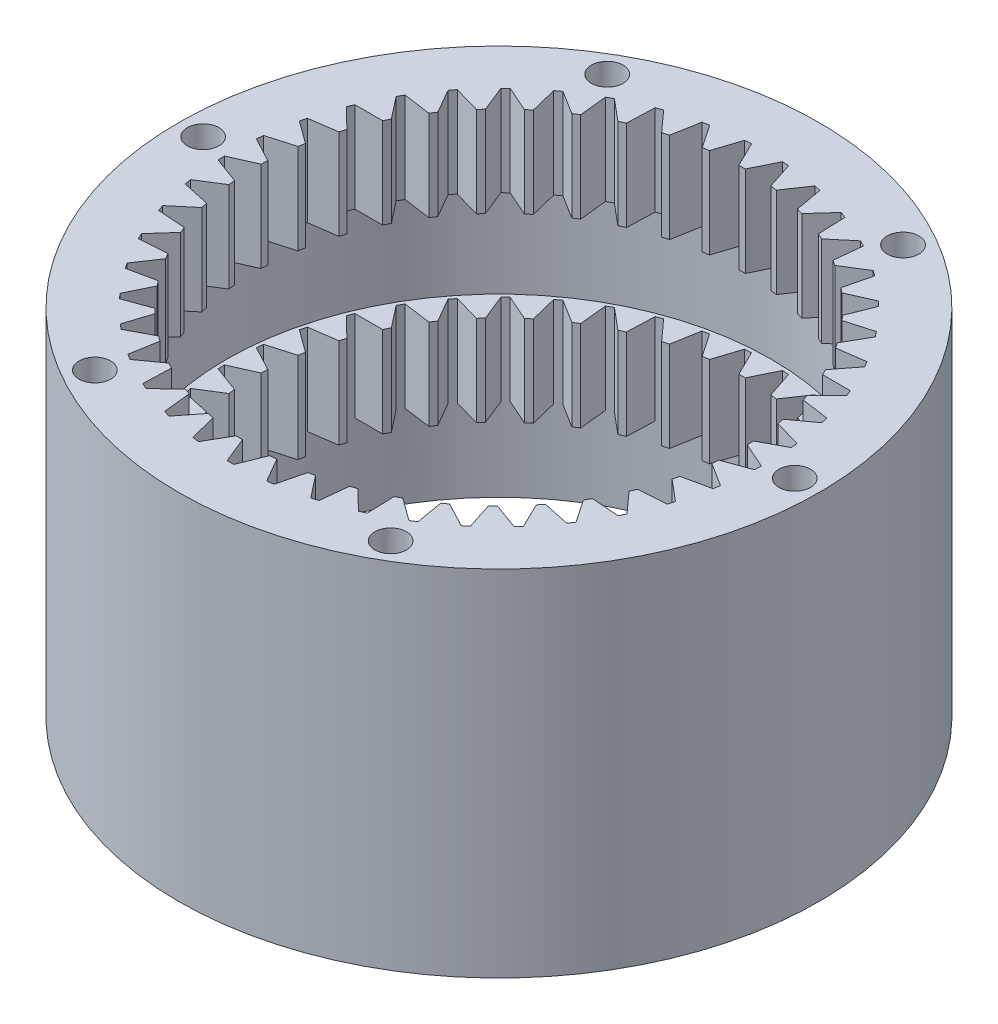
SolidWorks part; units mm, degrees
ref_plane "Plano frontal" through (0, 0, 0) normal (0, 0, 1) x (1, 0, 0)
ref_plane "Plano superior" through (0, 0, 0) normal (0, 1, 0) x (1, 0, 0)
ref_plane "Plano direito" through (0, 0, 0) normal (1, 0, 0) x (0, 0, -1)
sketch "Esboço1" plane through (0, 0, 0) normal (0, 1, 0) x (1, 0, 0)
  circle A0 centre (0, 0) radius 42.5
  circle A1 centre (0, 0) radius 35.626
  dimension "D1" = 85
  dimension "D2" = 71.252
extrude "Ressalto-extrusão1" add sketch "Esboço1" against normal blind 47
sketch "Esboço2" plane through (0, 0, 0) normal (0, 1, 0) x (1, 0, 0)
  line L0 (0, 35.626) -> (0, 32.258) construction
  line L1 (-0.4275, 32.258) -> (0.4275, 32.258)
  line L2 (-0.4275, 32.258) -> (-2.0474, 35.5671)
  line L3 (0.4275, 32.258) -> (2.0474, 35.5671)
  circle A0 centre (0, 0) radius 35.626 construction
  circle A2 centre (0, 0) radius 35.626
  arc A3 (2.0474, 35.5671) -> (-2.0474, 35.5671) centre (0, 0) ccw
  point P8 (0, 32.258)
  dimension "D1" = 3.368
  dimension "D2" = 0.855
  dimension "D3" = 26.084
  dimension "D4" = 0
extrude "Ressalto-extrusão2" add sketch "Esboço2" against normal blind 36
pattern_circular "PadrãoCircular2" count 45 over 360 about axis through (0, 0, 0) along (0, 1, 0) of "Ressalto-extrusão2"
ref_plane "Plano2" through (0, -12, 0) normal (0, 1, 0) x (1, 0, 0)
sketch "Esboço5" plane through (0, -12, 0) normal (0, 1, 0) x (1, 0, 0)
  circle A0 centre (0, 0) radius 36.126
  dimension "D1" = 72.252
extrude "Corte-extrusão1" cut sketch "Esboço5" against normal blind 12
sketch "Esboço6" plane through (0, -47, 0) normal (0, -1, 0) x (1, 0, 0)
  line L0 (0, 0) -> (0, 42.5) construction
  line L1 (0, 0) -> (19.625, 33.9915) construction
  circle A0 centre (0, 0) radius 42.5 construction
  circle A1 centre (19.625, 33.9915) radius 2.1
  dimension "D3" = 4.2
  dimension "D1" = 30
  dimension "D2" = 39.25
extrude "Corte-extrusão2" cut sketch "Esboço6" against normal blind 10
pattern_circular "PadrãoCircular3" count 6 over 360 about axis through (0, 0, 0) along (0, 1, 0) of "Corte-extrusão2"
ref_plane "Plano3" through (0, -23.5, 0) normal (0, -1, 0) x (-1, 0, 0)
mirror "Espelhar1" about plane through (0, -23.5, 0) normal (0, -1, 0) of "Corte-extrusão2", "PadrãoCircular3"
